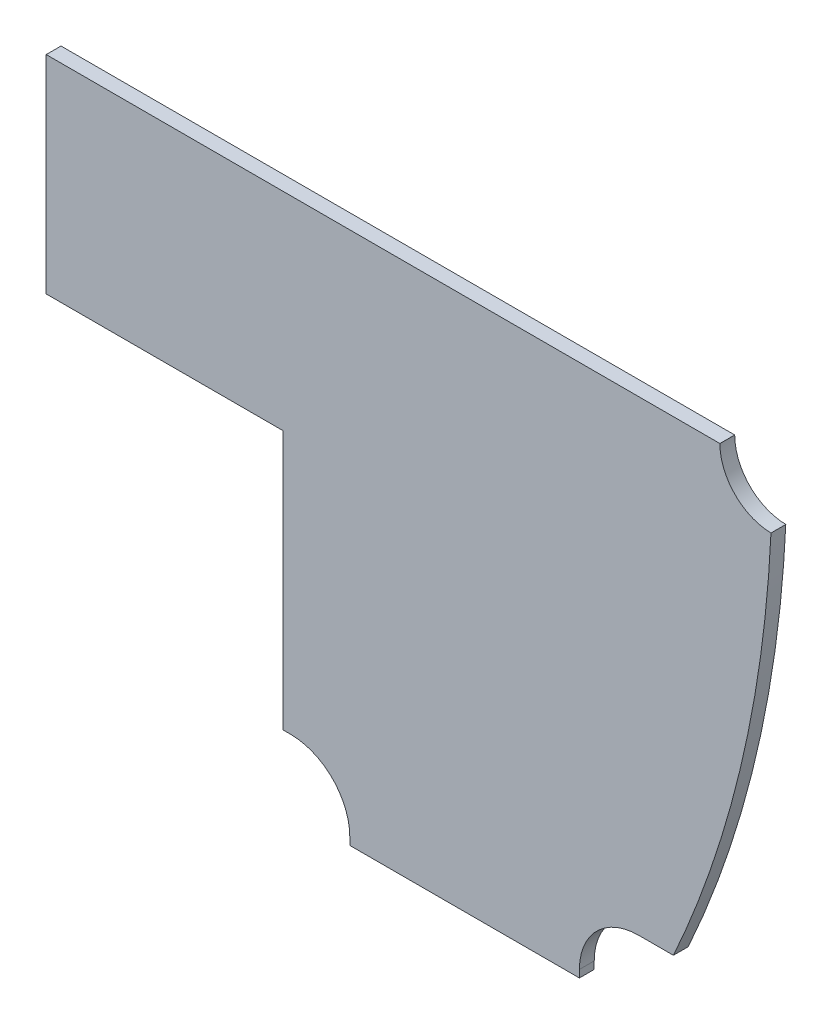
SolidWorks part; units mm, degrees
ref_plane "前视基准面" through (0, 0, 0) normal (0, 0, 1) x (1, 0, 0)
ref_plane "上视基准面" through (0, 0, 0) normal (0, 1, 0) x (1, 0, 0)
ref_plane "右视基准面" through (0, 0, 0) normal (1, 0, 0) x (0, 0, -1)
sketch "草图1" plane through (0, 0, 0) normal (0, 0, 1) x (1, 0, 0)
  line L13 (-61, -32) -> (-60.5, -32)
  line L14 (-61, -32) -> (-60.5, -32)
  line L15 (-56.5, -36) -> (-56.5, -36.5)
  line L16 (-56.5, -36) -> (-56.5, -36.5)
  line L17 (-40.995, -36.5) -> (-40.995, -36)
  line L18 (-40.995, -36.5) -> (-40.995, -36)
  line L19 (-31.5081, -0.5081) -> (-31.5081, -0.5)
  line L20 (-31.5081, -0.5081) -> (-31.5081, -0.5)
  line L26 (-72, -0.5) -> (-72, -14.5)
  line L27 (-72, -14.5) -> (-61, -14.5)
  line L28 (-61, -14.5) -> (-61, -32)
  line L29 (-56.5, -36.5) -> (-40.995, -36.5)
  line L30 (-36.995, -32) -> (-34.6481, -32)
  line L31 (-31.5081, -0.5) -> (-72, -0.5)
  line L32 (-77, -0.5) -> (-77, -14.5)
  line L33 (-77, -14.5) -> (-61, -14.5)
  line L34 (-61, -14.5) -> (-61, -32)
  line L35 (-56.5, -36.5) -> (-40.995, -36.5)
  line L36 (-36.995, -32) -> (-34.6481, -32)
  line L37 (-31.5081, -0.5) -> (-77, -0.5)
  arc A6 (-56.5, -36) -> (-60.5, -32) centre (-60.5, -36) ccw
  arc A7 (-36.995, -32) -> (-40.995, -36) centre (-36.995, -36) ccw
  arc A8 (-31.5081, -0.5081) -> (-28.0589, -4.0077) centre (-28.0081, -0.5081) ccw
  arc A9 (-56.5, -36) -> (-60.5, -32) centre (-60.5, -36) ccw
  arc A10 (-36.995, -32) -> (-40.995, -36) centre (-36.995, -36) ccw
  arc A11 (-31.5081, -0.5081) -> (-28.0589, -4.0077) centre (-28.0081, -0.5081) ccw
  spline S2 degree 3 poles (-2976.0262, 458.4921) (-965.9345, -100.9807) (-97.4198, -218.5603) (-31.6026, -24.1309) (-31.244, -22.9776) (-30.5849, -20.6579) (-30.284, -19.4906) (-29.7385, -17.1412) (-29.4937, -15.958) (-29.0608, -13.5859) (-28.8723, -12.3964) (0.0383, 201.2596) (-828.1475, 519.3027) (2900.0645, 274.0097) knots -20.891461 -20.891461 -20.891461 -20.891461 0.25 0.25 0.375 0.375 0.5 0.5 0.625 0.625 0.75 0.75 23.01488 23.01488 23.01488 23.01488 only from (-34.6481, -32) to (-28.0589, -4.0077)
  spline S3 degree 3 poles (-34.6481, -32) (-33.6492, -29.8015) (-32.7632, -27.5594) (-31.6026, -24.1309) (-31.244, -22.9776) (-30.5849, -20.6579) (-30.284, -19.4906) (-29.7385, -17.1412) (-29.4937, -15.958) (-29.0608, -13.5859) (-28.8723, -12.3964) (-28.3881, -8.818) (-28.1733, -6.419) (-28.0589, -4.0077) knots 0 0 0 0 0.25 0.25 0.375 0.375 0.5 0.5 0.625 0.625 0.75 0.75 1 1 1 1
  point P2 (-80.3083, -14.5)
  dimension "D2" = 16
  dimension "D1" = 1.5
extrude "凸台-拉伸1" add sketch "草图1" along normal blind 1
